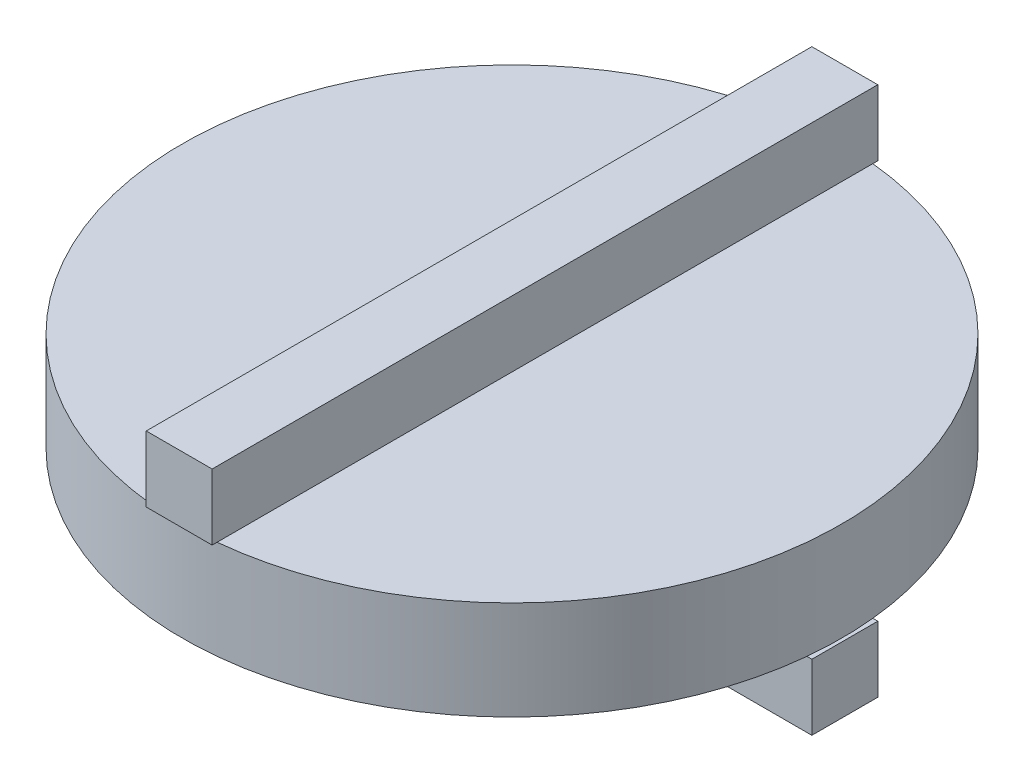
SolidWorks part; units mm, degrees
ref_plane "Front Plane" through (0, 0, 0) normal (0, 0, 1) x (1, 0, 0)
ref_plane "Top Plane" through (0, 0, 0) normal (0, 1, 0) x (1, 0, 0)
ref_plane "Right Plane" through (0, 0, 0) normal (1, 0, 0) x (0, 0, -1)
sketch "Sketch1" plane through (0, 0, 0) normal (0, 1, 0) x (1, 0, 0)
  circle A0 centre (0, 0) radius 50
  dimension "D1" = 100
extrude "Boss-Extrude1" add sketch "Sketch1" along normal blind 15
sketch "Sketch2" plane through (0, 15, 0) normal (0, 1, 0) x (1, 0, 0)
  line L0 (0, 0) -> (0, 50000) construction
  line L1 (0, 0) -> (-50000, 0) construction
  line L2 (-5, 50.5) -> (5, 50.5)
  line L3 (5, 50.5) -> (5, -50.5)
  line L4 (5, -50.5) -> (-5, -50.5)
  line L5 (-5, -50.5) -> (-5, 50.5)
  dimension "D1" = 101
  dimension "D2" = 50.5
  dimension "D3" = 10
  dimension "D4" = 5
extrude "Boss-Extrude2" add sketch "Sketch2" along normal blind 10
sketch "Sketch3" plane through (0, 0, 0) normal (0, -1, 0) x (1, 0, 0)
  line L0 (0, 0) -> (-50000, 0) construction
  line L1 (0, 0) -> (0, 50000) construction
  line L2 (-50.5, 5) -> (-50.5, -5)
  line L3 (-50.5, -5) -> (50.5, -5)
  line L4 (50.5, -5) -> (50.5, 5)
  line L5 (50.5, 5) -> (-50.5, 5)
  dimension "D1" = 10
  dimension "D2" = 5
  dimension "D3" = 101
  dimension "D4" = 50.5
extrude "Boss-Extrude3" add sketch "Sketch3" along normal blind 10
